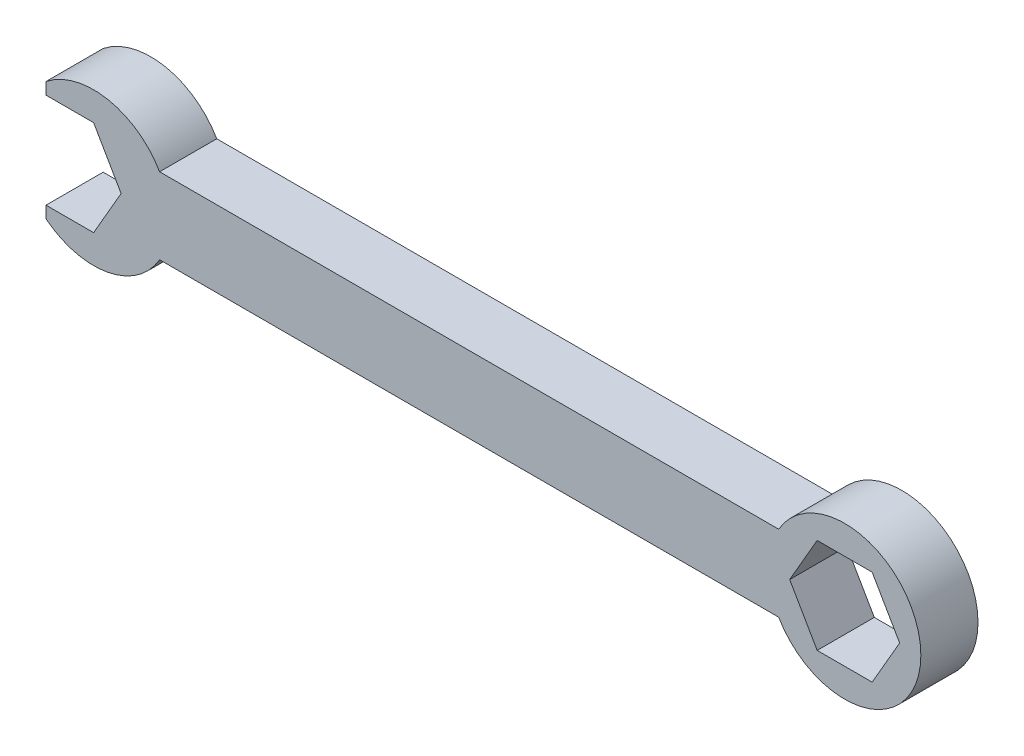
SolidWorks part; units mm, degrees
ref_plane "Front Plane" through (0, 0, 0) normal (0, 0, 1) x (1, 0, 0)
ref_plane "Top Plane" through (0, 0, 0) normal (0, 1, 0) x (1, 0, 0)
ref_plane "Right Plane" through (0, 0, 0) normal (1, 0, 0) x (0, 0, -1)
sketch "Sketch2" plane through (0, 0, 0) normal (0, 0, 1) x (1, 0, 0)
  line L0 (0, 0) -> (99.6853, 0) construction
  line L7 (0, 0) -> (0, 28.0393) construction
  line L8 (0, 28.0393) -> (0, -20.8451) construction
  line L9 (0, 0) -> (-10.0162, 0) construction
  line L10 (-3.6662, 6.35) -> (-3.6662, -6.35) construction
  line L11 (0, 0) -> (-3.6662, 6.35)
  line L12 (-3.6662, 6.35) -> (-10.0162, 6.35)
  line L15 (-10.0162, -6.35) -> (-3.6662, -6.35)
  line L16 (-3.6662, -6.35) -> (0, 0)
  line L17 (-10.0162, 11.1599) -> (-10.0162, 0) construction
  line L18 (-10.0162, 7.9311) -> (-10.0162, 6.35)
  line L19 (-10.0162, -7.9311) -> (-10.0162, -6.35)
  line L20 (-10.0162, -6.35) -> (-10.0162, -9.9954) construction
  line L21 (-12.8316, -3.175) -> (-10.9985, -6.35) [skipped]
  line L22 (-12.8316, 3.175) -> (-13.6828, 1.7006) [skipped]
  line L23 (5.1326, 5.08) -> (87.6826, 5.08)
  line L24 (5.1326, -5.08) -> (87.6826, -5.08)
  line L26 (103.8138, 0) -> (100.1476, 6.35)
  line L27 (100.1476, 6.35) -> (92.8153, 6.35)
  line L28 (92.8153, 6.35) -> (89.1491, 0)
  line L29 (89.1491, 0) -> (92.8153, -6.35)
  line L30 (92.8153, -6.35) -> (100.1476, -6.35)
  line L31 (100.1476, -6.35) -> (103.8138, 0)
  arc A0 (-7.3323, -6.35) -> (-7.3323, 6.35) centre (-7.3323, 0) ccw construction
  arc A2 (-10.0162, -7.9311) -> (-10.0162, 7.9311) centre (-3.6662, 0) ccw
  circle A4 centre (96.4815, 0) radius 10.16
  circle A5 centre (96.4815, 0) radius 6.35 construction
  point P20 (-10.9985, -6.35)
  dimension "D2" = 6.35
  dimension "D4" = 10.16
  dimension "D1" = 12.7
  dimension "D5" = 20.32
  dimension "D3" = 10.16
  dimension "D6" = 82.55
  dimension "D7" = 12.7
extrude "Boss-Extrude1" add sketch "Sketch2" along normal blind 7.62 contours A4 L23 A2 L24 | A2 L18 L12 L11 L16 L15 L19 | A4 L31 L30 L29 L28 L27 L26
